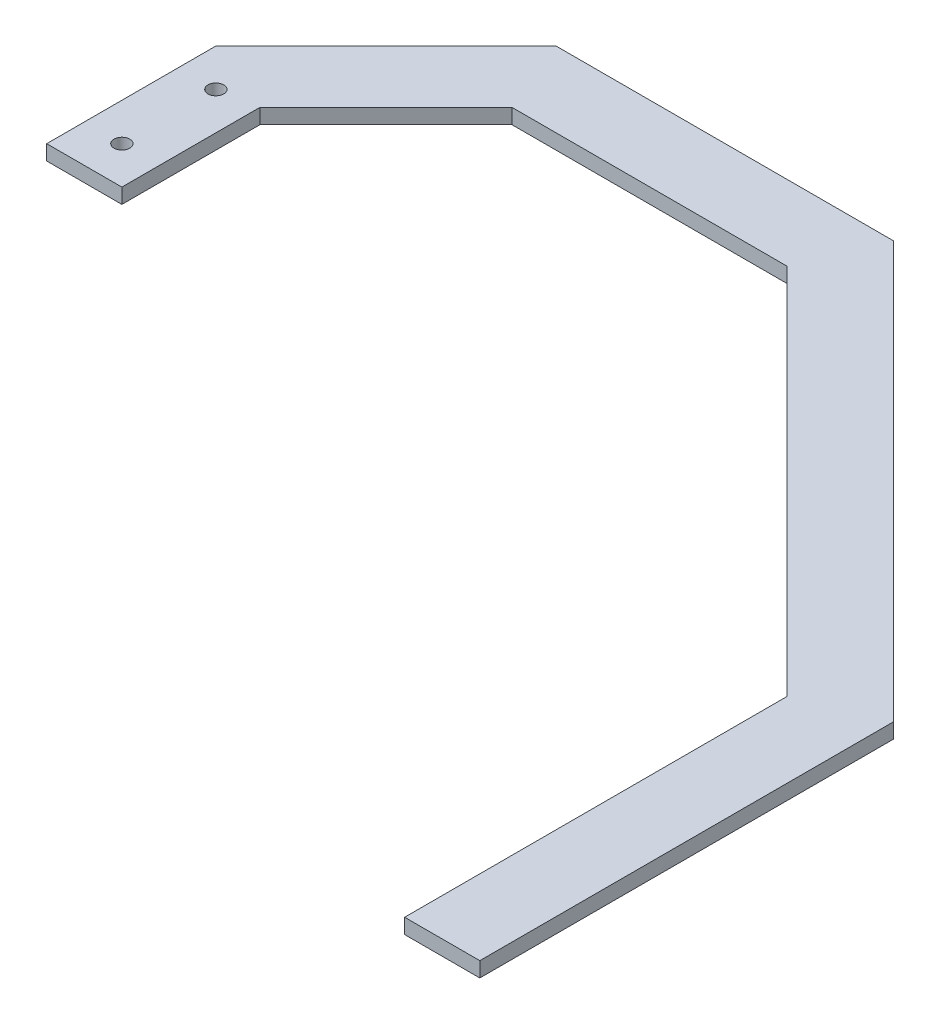
SolidWorks part; units mm, degrees
ref_plane "前视基准面" through (0, 0, 0) normal (0, 0, 1) x (1, 0, 0)
ref_plane "上视基准面" through (0, 0, 0) normal (0, 1, 0) x (1, 0, 0)
ref_plane "右视基准面" through (0, 0, 0) normal (1, 0, 0) x (0, 0, -1)
sketch "草图1" plane through (0, 0, 0) normal (0, 1, 0) x (1, 0, 0)
  line L0 (0, 22.5) -> (20, 22.5) construction
  line L2 (20, 0) -> (0, 0)
  line L3 (0, 0) -> (0, 45)
  line L4 (0, 45) -> (45.25, 90.25)
  line L8 (53.5343, 70.25) -> (20, 36.7157)
  line L9 (20, 36.7157) -> (20, 0)
  line L10 (10, 22.5) -> (10, 0) construction
  line L11 (45.25, 90.25) -> (134.9676, 90.25)
  line L12 (134.9676, 90.25) -> (245.8244, -20.6068)
  line L13 (245.8244, -20.6068) -> (245.8244, -130.6068)
  line L14 (245.8244, -130.6068) -> (225.8244, -130.6068)
  line L15 (225.8244, -130.6068) -> (225.8244, -28.8911)
  line L16 (225.8244, -28.8911) -> (126.6833, 70.25)
  line L17 (126.6833, 70.25) -> (53.5343, 70.25)
  line L18 (0, 0) -> (0, -140) construction
  line L24 (69.7237, 90.25) -> (69.7237, 70.25) construction
  line L27 (69.7237, 80.25) -> (79.5, 80.25) construction
  circle A0 centre (10, 10) radius 2.1
  circle A1 centre (10, 35) radius 2.1
  point P23 (79.5, 80.25)
  point P28 (69.7237, 89.2478)
  dimension "D4" = 4.2
  dimension "D5" = 25
  dimension "D6" = 20
  dimension "D1" = 45
  dimension "D2" = 20
  dimension "D3" = 45
  dimension "D7" = 20
  dimension "D8" = 20
  dimension "D9" = 110
  dimension "D10" = 140
  dimension "D11" = 20
  dimension "D12" = 135
extrude "凸台-拉伸1" add sketch "草图1" along normal blind 4
